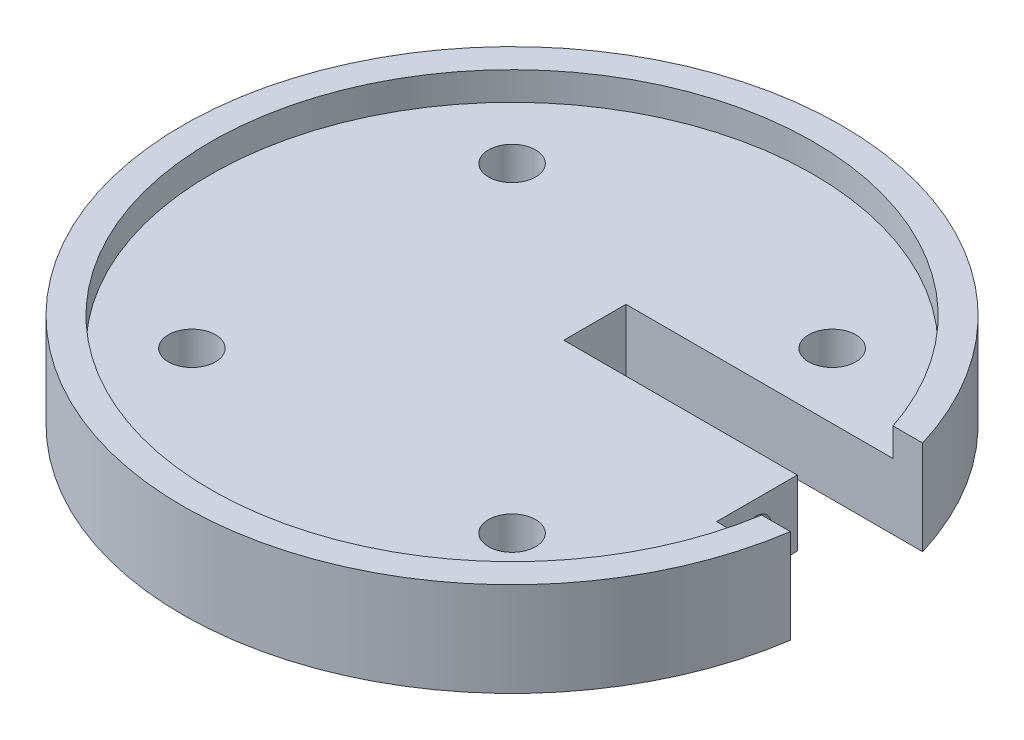
SolidWorks part; units mm, degrees
ref_plane "Front Plane" through (0, 0, 0) normal (0, 0, 1) x (1, 0, 0)
ref_plane "Top Plane" through (0, 0, 0) normal (0, 1, 0) x (1, 0, 0)
ref_plane "Right Plane" through (0, 0, 0) normal (1, 0, 0) x (0, 0, -1)
sketch "Sketch1" plane through (0, 0, 0) normal (0, 1, 0) x (1, 0, 0)
  circle A0 centre (0, 0) radius 35
  dimension "D1" = 70
extrude "Boss-Extrude1" add sketch "Sketch1" along normal blind 10
sketch "Sketch27" plane through (0, 10, 0) normal (0, 1, 0) x (1, 0, 0)
  line L1 (35.2528, 3.4921) -> (26.8023, 3.4921)
  line L2 (35.2528, 3.4921) -> (35.2528, -5.0808)
  line L3 (35.2528, -5.0808) -> (26.8023, -5.0808)
  line L4 (26.8023, 3.4921) -> (26.8023, -5.0808)
  line L5 (35.2528, 3.4921) -> (26.8023, -5.0808) construction
  line L6 (35.2528, -5.0808) -> (26.8023, 3.4921) construction
  point P0 (31.0276, -0.7944)
extrude "Cut-Extrude8" cut sketch "Sketch27" against normal through all
sketch "Sketch28" plane through (0, 10, 0) normal (0, 1, 0) x (1, 0, 0)
sketch "Sketch34" plane through (0, 10, 0) normal (0, 1, 0) x (1, 0, 0)
  circle A0 centre (-17, 17) radius 2.5
extrude "Cut-Extrude9" cut sketch "Sketch34" against normal through all and the other way through all
sketch "Sketch35" plane through (0, 0, 0) normal (0, -1, 0) x (-1, 0, 0)
  circle A0 centre (-17, 17) radius 2.5
extrude "Cut-Extrude10" cut sketch "Sketch35" against normal through all
sketch "Sketch36" plane through (0, 0, 0) normal (0, -1, 0) x (-1, 0, 0)
  circle A0 centre (17, -17) radius 2.5
extrude "Cut-Extrude11" cut sketch "Sketch36" against normal through all
sketch "Sketch37" plane through (0, 0, 0) normal (0, -1, 0) x (1, 0, 0)
  circle A0 centre (17, 17) radius 2.5
extrude "Cut-Extrude12" cut sketch "Sketch37" against normal through all
sketch "Sketch39" plane through (0, 10, 0) normal (0, 1, 0) x (1, 0, 0)
  circle A0 centre (0, 0) radius 32
extrude "Cut-Extrude14" cut sketch "Sketch39" against normal blind 3
sketch "Sketch40" plane through (26.8023, 0, 0) normal (1, 0, 0) x (0, 0, -1)
  circle A0 centre (-0.8474, 3.8011) radius 1.6
extrude "Cut-Extrude16" cut sketch "Sketch40" against normal blind 35 contours A0
hole_wizard "Ø6.0mm Dowel Hole6" positions "Sketch48" profile "Sketch49" hole size "Ø6.0" standard "DIN"
sketch "Sketch48" plane through (-8.1977, 0, 0) normal (1, 0, 0) x (0, 0, -1)
  point P0 (-0.8474, 3.8011)
sketch "Sketch49" plane through (-8.1977, 3.8011, 0.8474) normal (0, 1, 0) x (0, 0, -1)
  line L0 (0, 0) -> (0, 26.8023)
  line L1 (0, 26.8023) -> (3, 26.8023)
  line L2 (3, 26.8023) -> (3, 0)
  line L5 (3, 0) -> (0, 0)
  line L11 (0, -6.35) -> (0, 107.95) construction
  dimension "Thru Hole Dia." = 6
  dimension "Thru Hole Depth" = 26.8023
sketch "Sketch52" plane through (0, 0, 0) normal (0, -1, 0) x (-1, 0, 0)
  line L0 (-26.8023, 3.4921) -> (-1.9998, 3.4921)
  line L1 (-1.9998, 3.4921) -> (-1.9998, 10.0921)
  line L2 (-1.9998, 10.0921) -> (-33.5134, 10.0921)
  line L3 (-33.5134, 10.0921) -> (-39.472, 10.0921)
  line L4 (-39.472, 10.0921) -> (-42.0193, 10.0921)
  line L5 (-42.0193, 10.0921) -> (-42.0193, 3.4921)
  line L6 (-42.0193, 3.4921) -> (-26.8023, 3.4921)
  arc A0 (-34.6293, -5.0808) -> (-34.8254, 3.4921) centre (0, 0) ccw construction
extrude "Cut-Extrude18" cut sketch "Sketch52" against normal through all
